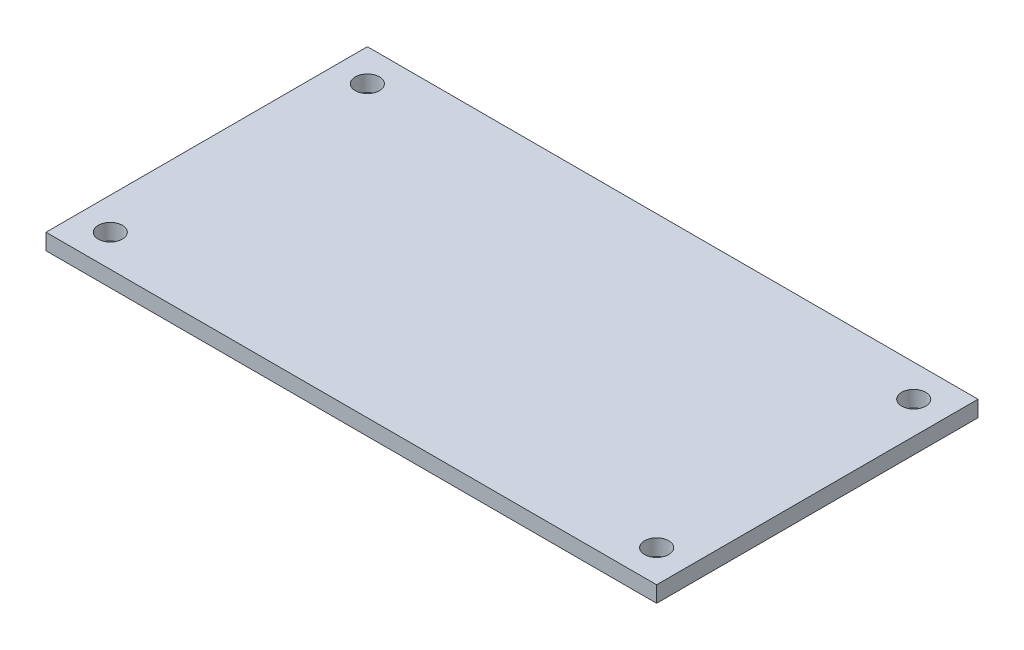
SolidWorks part; units mm, degrees
ref_plane "前视基准面" through (0, 0, 0) normal (0, 0, 1) x (1, 0, 0)
ref_plane "上视基准面" through (0, 0, 0) normal (0, 1, 0) x (1, 0, 0)
ref_plane "右视基准面" through (0, 0, 0) normal (1, 0, 0) x (0, 0, -1)
other "Configuration Table"
sketch "草图1" plane through (0, 0, 0) normal (0, 1, 0) x (1, 0, 0)
  line L0 (-38, 20) -> (38, 20)
  line L1 (38, 20) -> (38, -20)
  line L2 (38, -20) -> (-38, -20)
  line L3 (-38, -20) -> (-38, 20)
  line L4 (0, 20) -> (0, -20) construction
  line L5 (-38, 0) -> (38, 0) construction
  circle A0 centre (34, 16) radius 1.5
  circle A1 centre (34, -16) radius 1.5
  circle A2 centre (-34, -16) radius 1.5
  circle A3 centre (-34, 16) radius 1.5
  point P2 (0, 20)
  point P5 (-38, 0)
  dimension "D3" = 3
  dimension "D1" = 76
  dimension "D2" = 40
  dimension "D4" = 68
  dimension "D5" = 32
extrude "凸台-拉伸1" add sketch "草图1" along normal blind 2
